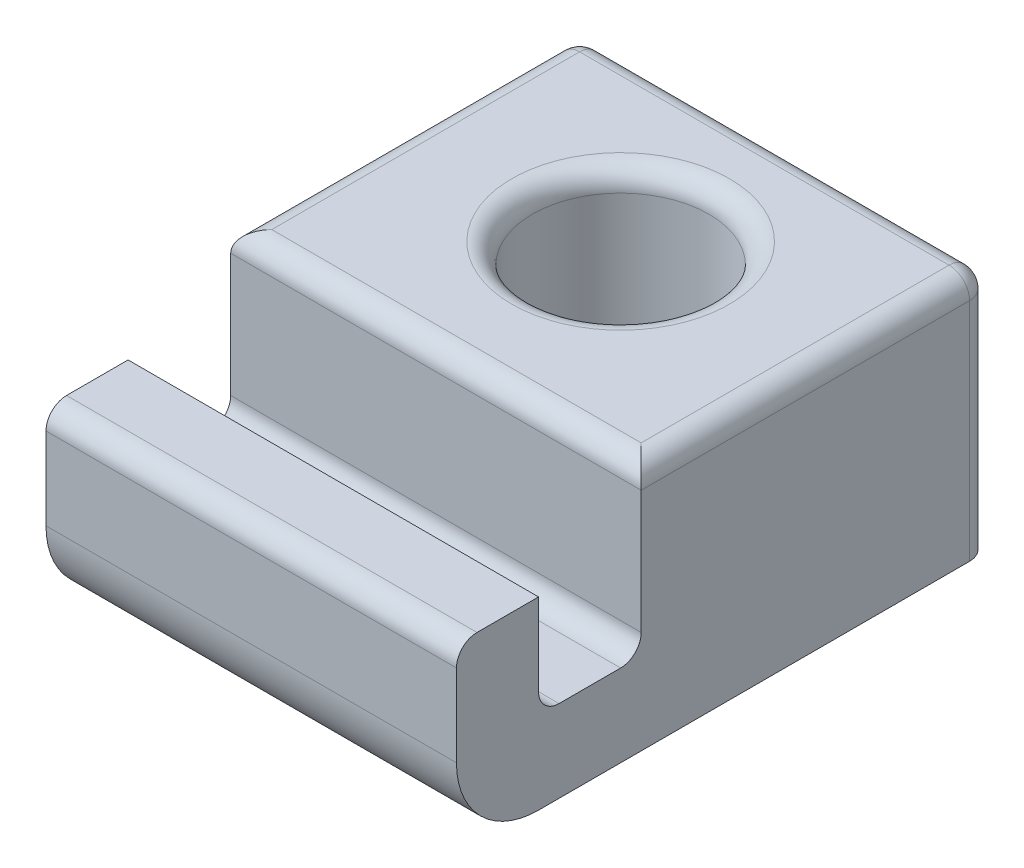
SolidWorks part; units mm, degrees
ref_plane "Front Plane" through (0, 0, 0) normal (0, 0, 1) x (1, 0, 0)
ref_plane "Top Plane" through (0, 0, 0) normal (0, 1, 0) x (1, 0, 0)
ref_plane "Right Plane" through (0, 0, 0) normal (1, 0, 0) x (0, 0, -1)
sketch "Sketch1" plane through (0, 0, 0) normal (0, 1, 0) x (1, 0, 0)
  line L1 (-5, -6.5) -> (5, -6.5)
  line L2 (-5, -6.5) -> (-5, 6.5)
  line L3 (-5, 6.5) -> (5, 6.5)
  line L4 (5, -6.5) -> (5, 6.5)
  line L5 (-5, -6.5) -> (5, 6.5) construction
  line L6 (-5, 6.5) -> (5, -6.5) construction
  point P0 (0, 0)
  dimension "D1" = 10
  dimension "D2" = 13
extrude "Boss-Extrude1" add sketch "Sketch1" along normal blind 2
sketch "Sketch2" plane through (0, 2, 0) normal (0, 1, 0) x (1, 0, 0)
  line L0 (5, -6.5) -> (5, 6.5) construction
  line L1 (-5, -6.5) -> (5, -6.5)
  line L2 (-5, -6.5) -> (-5, -4.5)
  line L3 (-5, -4.5) -> (5, -4.5)
  line L4 (5, -6.5) -> (5, -4.5)
  dimension "D1" = 2
extrude "Boss-Extrude2" add sketch "Sketch2" along normal blind 2.5
fillet "Fillet1" radius 2 1 edges at (0, 0, 6.5)
fillet "Fillet2" radius 0.5 1 edges at (0, 4.5, 6.5)
sketch "Sketch3" plane through (0, 2, 0) normal (0, 1, 0) x (1, 0, 0)
  line L0 (5, -4.5) -> (5, 6.5) construction
  line L1 (-5, 6.5) -> (5, 6.5)
  line L2 (-5, 6.5) -> (-5, -2)
  line L3 (-5, -2) -> (5, -2)
  line L4 (5, 6.5) -> (5, -2)
  dimension "D1" = 8.5
extrude "Boss-Extrude3" add sketch "Sketch3" along normal blind 4
sketch "Sketch4" plane through (0, 6, 0) normal (0, 1, 0) x (1, 0, 0)
  circle A0 centre (0, 2.5) radius 2.15
  dimension "D1" = 4.3
  dimension "D2" = 2.5
extrude "Cut-Extrude1" cut sketch "Sketch4" against normal up to next
fillet "Fillet3" radius 0.5 8 edges at (0, 2, 4.5) (0, 2, 2) (0, 6, 2) (5, 6, -2.25) (-5, 6, -2.25) (0, 6, -6.5) (5, 3, -6.5) (-5, 3, -6.5)
fillet "Fillet4" radius 0.5 1 edges at (0, 6, -0.35)
